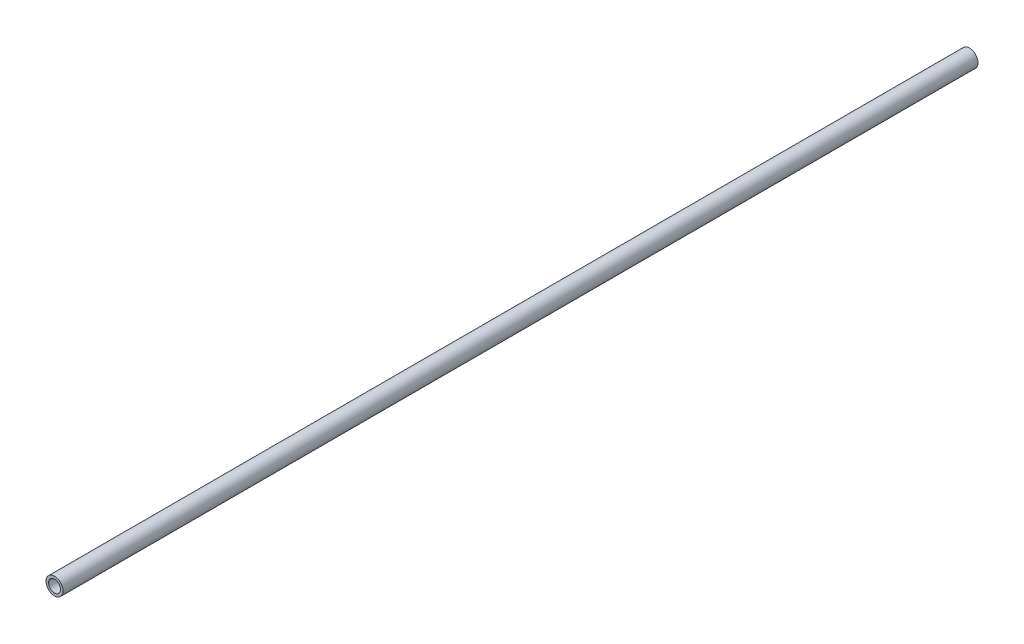
SolidWorks part; units mm, degrees
ref_plane "Front Plane" through (0, 0, 0) normal (1, 0, 0) x (0, 1, 0)
ref_plane "Top Plane" through (0, 0, 0) normal (0, 0, 1) x (0, 1, 0)
ref_plane "Right Plane" through (0, 0, 0) normal (0, 1, 0) x (-1, 0, 0)
sketch "Sketch1" plane through (0, 0, 0) normal (0, 0, 1) x (0, 1, 0)
  circle A0 centre (0, 0) radius 15.875
  circle A1 centre (0, 0) radius 11.1
  dimension "D1" = 31.75
  dimension "D2" = 22.2
extrude "Boss-Extrude1" add sketch "Sketch1" along normal blind 1700
equation "\"OD\"= 1.25in"
equation "\"ID\"= 22.2"
equation "\"D1@Sketch1\"=\"OD\""
equation "\"D2@Sketch1\"=\"ID\""
equation "\"L\"= 1700mm"
equation "\"D1@Boss-Extrude1\"=\"L\""
